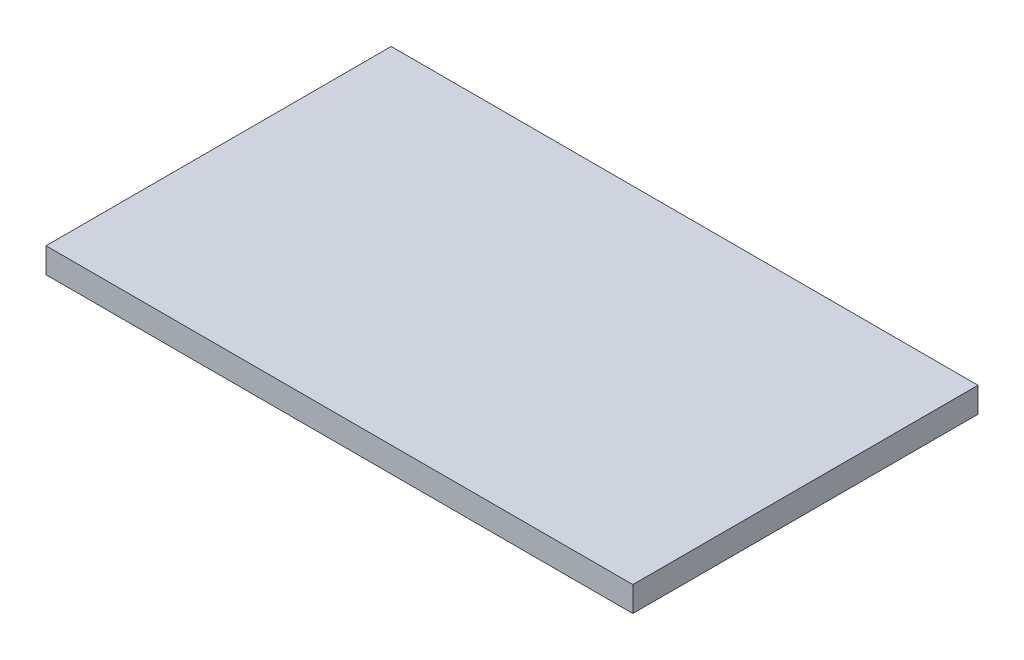
SolidWorks part; units mm, degrees
ref_plane "Front Plane" through (0, 0, 0) normal (0, 0, 1) x (1, 0, 0)
ref_plane "Top Plane" through (0, 0, 0) normal (0, 1, 0) x (1, 0, 0)
ref_plane "Right Plane" through (0, 0, 0) normal (1, 0, 0) x (0, 0, -1)
sketch "Sketch1" plane through (0, 0, 0) normal (0, 1, 0) x (1, 0, 0)
  line L1 (-18.7, -11) -> (18.7, -11)
  line L2 (-18.7, -11) -> (-18.7, 11)
  line L3 (-18.7, 11) -> (18.7, 11)
  line L4 (18.7, -11) -> (18.7, 11)
  line L5 (-18.7, -11) -> (18.7, 11) construction
  line L6 (-18.7, 11) -> (18.7, -11) construction
  point P0 (0, 0)
  dimension "D1" = 37.4
  dimension "D2" = 22
extrude "Boss-Extrude1" add sketch "Sketch1" along normal mid plane 1.6
